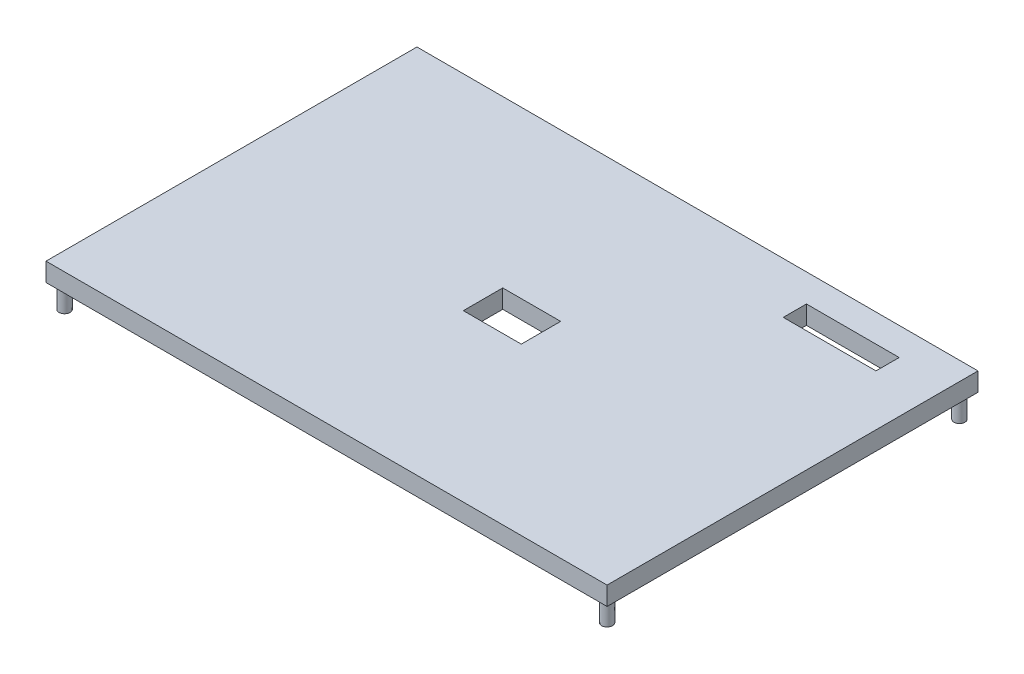
SolidWorks part; units mm, degrees
ref_plane "Front Plane" through (0, 0, 0) normal (0, 0, 1) x (1, 0, 0)
ref_plane "Top Plane" through (0, 0, 0) normal (0, 1, 0) x (1, 0, 0)
ref_plane "Right Plane" through (0, 0, 0) normal (1, 0, 0) x (0, 0, -1)
sketch "Sketch1" plane through (0, 0, 0) normal (0, 1, 0) x (1, 0, 0)
  line L1 (-60.5, -40) -> (60.5, -40)
  line L2 (-60.5, -40) -> (-60.5, 40)
  line L3 (-60.5, 40) -> (60.5, 40)
  line L4 (60.5, -40) -> (60.5, 40)
  line L5 (-60.5, -40) -> (60.5, 40) construction
  line L6 (-60.5, 40) -> (60.5, -40) construction
  line L7 (29.5, 34) -> (49.5, 34)
  line L8 (29.5, 34) -> (29.5, 29)
  line L9 (29.5, 29) -> (49.5, 29)
  line L10 (49.5, 34) -> (49.5, 29)
  line L11 (-6.25, -4.25) -> (6.25, -4.25)
  line L12 (-6.25, -4.25) -> (-6.25, 4.25)
  line L13 (-6.25, 4.25) -> (6.25, 4.25)
  line L14 (6.25, -4.25) -> (6.25, 4.25)
  line L15 (-6.25, -4.25) -> (6.25, 4.25) construction
  line L16 (-6.25, 4.25) -> (6.25, -4.25) construction
  point P0 (0, 0)
  point P10 (0, 0)
  dimension "D1" = 121
  dimension "D2" = 80
  dimension "D3" = 5
  dimension "D4" = 20
  dimension "D5" = 11
  dimension "D6" = 6
  dimension "D7" = 12.5
  dimension "D8" = 8.5
extrude "Boss-Extrude1" add sketch "Sketch1" along normal blind 4
sketch "Sketch4" plane through (0, 0, 0) normal (0, -1, 0) x (1, 0, 0)
  line L0 (-60.5, -40) -> (-58.5, -40) construction
  line L1 (60.5, -40) -> (-60.5, -40) construction
  line L2 (-58.5, -40) -> (-58.5, -38) construction
  line L3 (55, 0) -> (-55, 0) construction
  line L4 (0, -55) -> (0, 55) construction
  circle A0 centre (-58.5, -38) radius 1.185
  circle A1 centre (-58.5, 38) radius 1.185
  circle A2 centre (58.5, -38) radius 1.185
  circle A3 centre (58.5, 38) radius 1.185
  dimension "D3" = 2.37
  dimension "D1" = 2
  dimension "D2" = 2
extrude "Boss-Extrude2" add sketch "Sketch4" along normal blind 5
